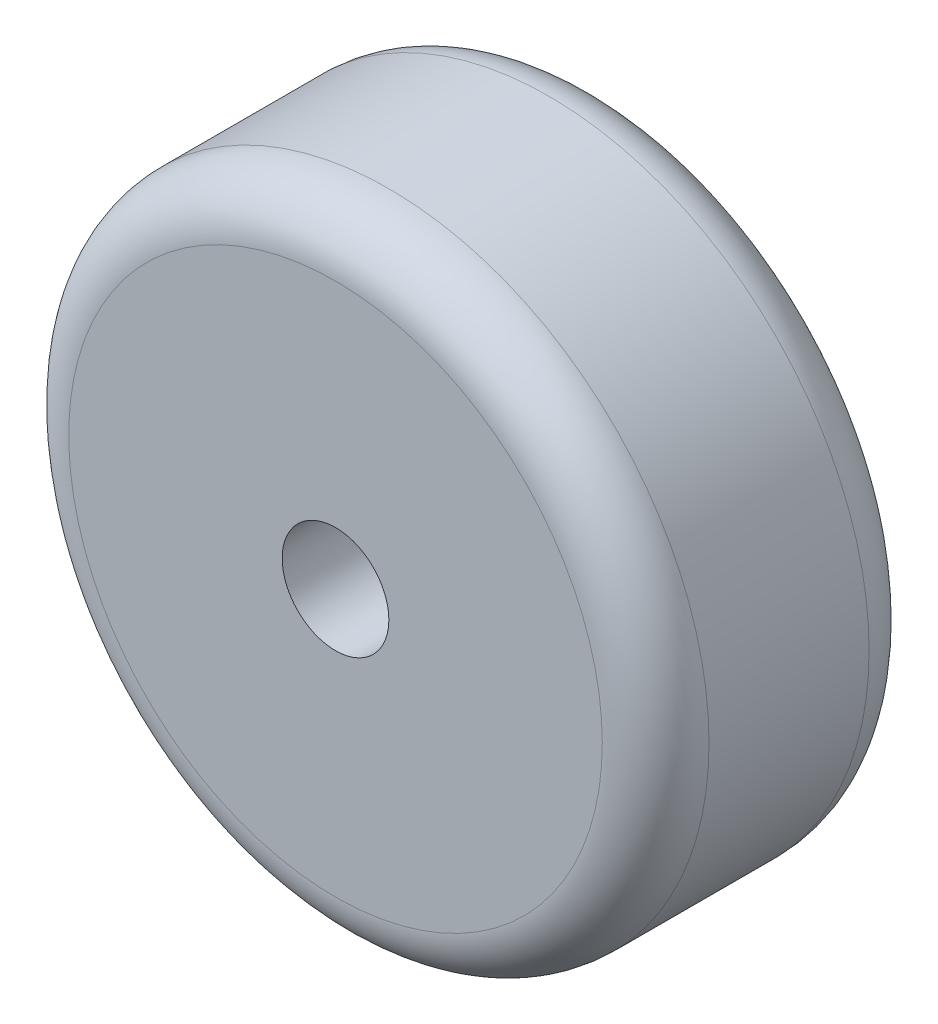
SolidWorks part; units mm, degrees
material "ABS"
ref_plane "Front Plane" through (0, 0, 0) normal (0, 0, 1) x (1, 0, 0)
ref_plane "Top Plane" through (0, 0, 0) normal (0, 1, 0) x (1, 0, 0)
ref_plane "Right Plane" through (0, 0, 0) normal (1, 0, 0) x (0, 0, -1)
sketch "Sketch1" plane through (0, 0, 0) normal (0, 0, 1) x (1, 0, 0)
  circle A1 centre (0, 491.0002) radius 1
  circle A2 centre (0, 491.0002) radius 6
  dimension "D1" = 5
extrude "Boss-Extrude1" add sketch "Sketch1" along normal blind 5
fillet "Fillet1" radius 1 2 edges at (6, 491.0002, 5) (6, 491.0002, 0)
